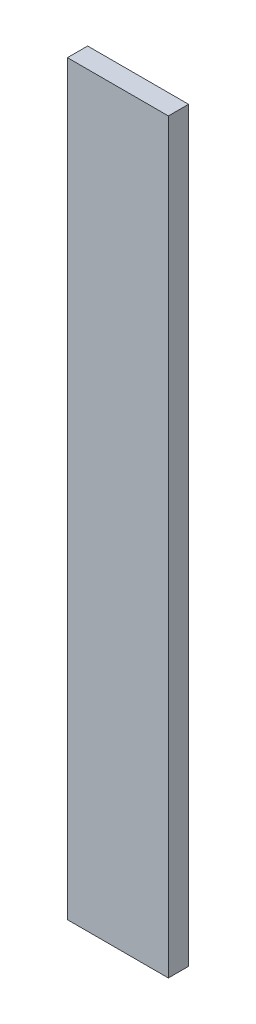
SolidWorks part; units mm, degrees
ref_plane "前视基准面" through (0, 0, 0) normal (0, 0, 1) x (1, 0, 0)
ref_plane "上视基准面" through (0, 0, 0) normal (0, 1, 0) x (1, 0, 0)
ref_plane "右视基准面" through (0, 0, 0) normal (1, 0, 0) x (0, 0, -1)
other "Configuration Table"
sketch "草图1" plane through (0, 0, 120.0175) normal (0, 0, -1) x (-1, 0, 0)
  line L0 (69.0532, 40.0354) -> (-51.6217, 40.0354) construction
  line L1 (-50.6217, 39.0354) -> (-40.6217, 39.0354)
  line L2 (-50.6217, 39.0354) -> (-50.6217, -34.9394)
  line L3 (-50.6217, -34.9394) -> (-40.6217, -34.9394)
  line L4 (-40.6217, 39.0354) -> (-40.6217, -34.9394)
  line L5 (-51.6217, -35.9394) -> (69.0532, -35.9394) construction
  line L6 (-51.6217, 40.0354) -> (-51.6217, -35.9394) construction
  dimension "D1" = 1
  dimension "D2" = 1
  dimension "D3" = 1
  dimension "D4" = 10
extrude "凸台-拉伸1" add sketch "草图1" along normal blind 2
